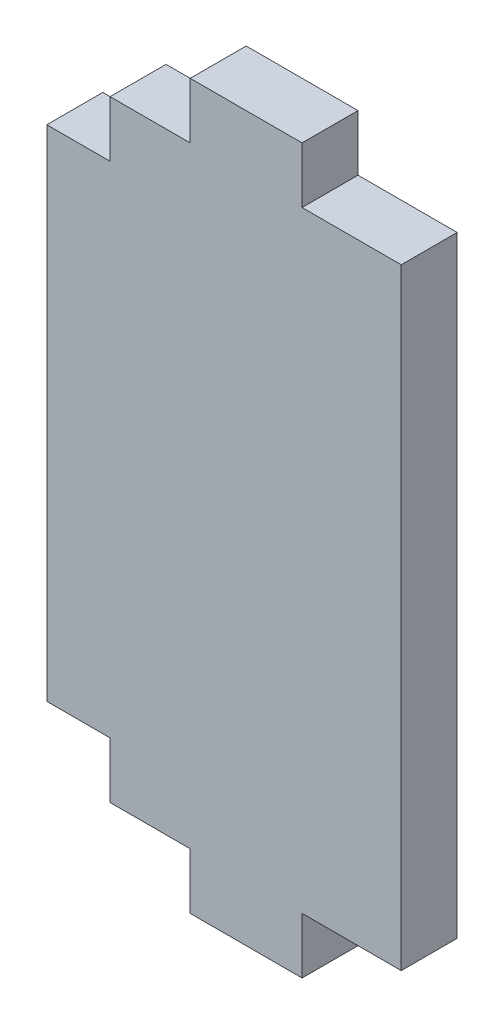
SolidWorks part; units mm, degrees
ref_plane "Front" through (0, 0, 0) normal (0, 0, 1) x (1, 0, 0)
ref_plane "Top" through (0, 0, 0) normal (0, 1, 0) x (1, 0, 0)
ref_plane "Right" through (0, 0, 0) normal (1, 0, 0) x (0, 0, -1)
sketch "Sketch1" plane through (0, 0, 0) normal (0, 0, 1) x (1, 0, 0)
  line L0 (-1235.8336, -48.5075) -> (-1235.8336, -81.2775)
  line L1 (-1241.1494, -81.2775) -> (-1235.8336, -81.2775)
  line L2 (-1241.1494, -84.2775) -> (-1241.1494, -81.2775)
  line L3 (-1251.4419, -81.2775) -> (-1247.1453, -81.2775)
  line L4 (-1251.4419, -78.2775) -> (-1251.4419, -81.2775)
  line L5 (-1254.8336, -78.2775) -> (-1251.4419, -78.2775)
  line L6 (-1247.1453, -81.2775) -> (-1247.1453, -84.2775)
  line L7 (-1254.8336, -78.2775) -> (-1254.8336, -51.5075)
  line L8 (-1247.1453, -84.2775) -> (-1241.1494, -84.2775)
  line L10 (-1247.1453, -45.5075) -> (-1241.1494, -45.5075)
  line L11 (-1247.1453, -48.5075) -> (-1247.1453, -45.5075)
  line L12 (-1254.8336, -51.5075) -> (-1251.4419, -51.5075)
  line L13 (-1251.4419, -51.5075) -> (-1251.4419, -48.5075)
  line L14 (-1251.4419, -48.5075) -> (-1247.1453, -48.5075)
  line L15 (-1241.1494, -45.5075) -> (-1241.1494, -48.5075)
  line L16 (-1241.1494, -48.5075) -> (-1235.8336, -48.5075)
  line L17 (-1254.8336, -64.8925) -> (-1235.8336, -64.8925) construction
  dimension "D1" = 90
  dimension "D2" = 90
  dimension "D3" = 32.77
  dimension "D4" = 3
  dimension "D5" = 3
  dimension "D6" = 32.77
  dimension "D7" = 4.2965
  dimension "D8" = 19
  dimension "D9" = 5.9959
  dimension "D10" = 5.3159
extrude "Base-Extrude" add sketch "Sketch1" along normal blind 3
